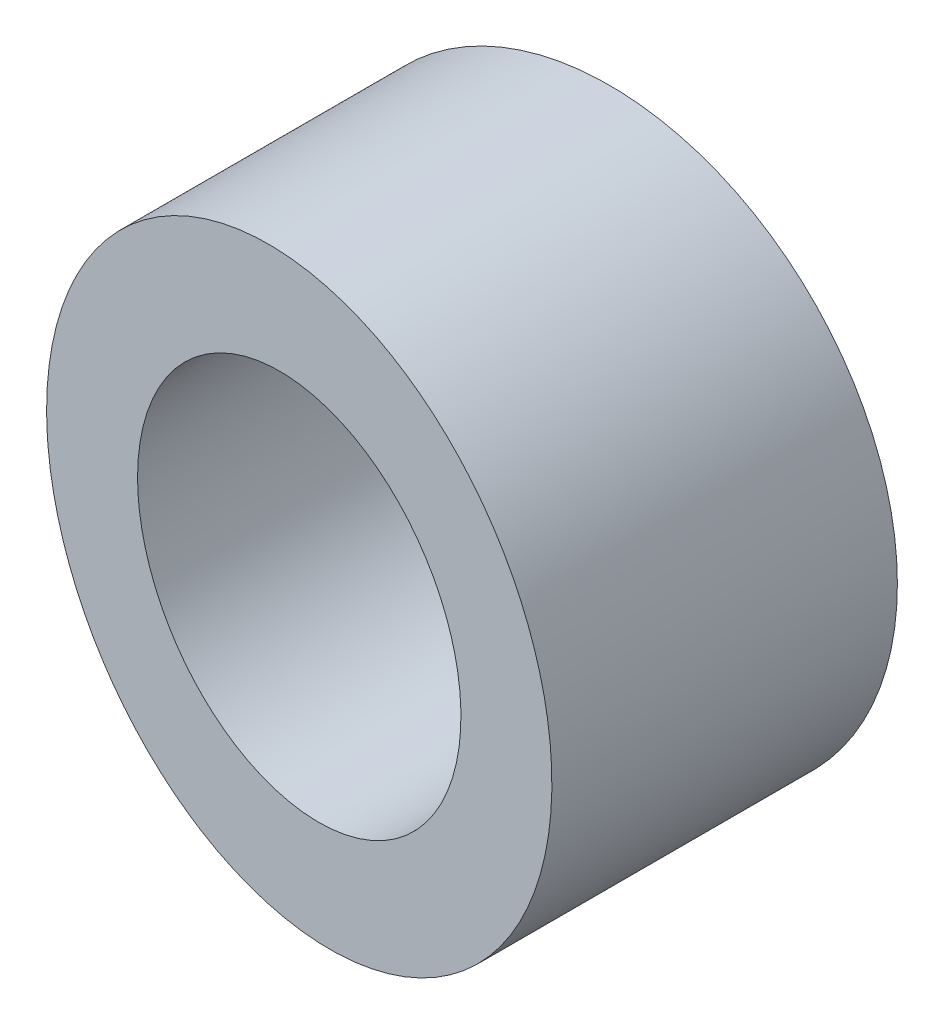
SolidWorks part; units mm, degrees
ref_plane "Front Plane" through (0, 0, 0) normal (0, 0, 1) x (1, 0, 0)
ref_plane "Top Plane" through (0, 0, 0) normal (0, 1, 0) x (1, 0, 0)
ref_plane "Right Plane" through (0, 0, 0) normal (1, 0, 0) x (0, 0, -1)
sketch "Sketch1" plane through (0, 0, 0) normal (0, 0, 1) x (1, 0, 0)
  circle A0 centre (0, 0) radius 12.5
  circle A1 centre (0, 0) radius 8
  dimension "D1" = 25
  dimension "D2" = 16
extrude "Boss-Extrude1" add sketch "Sketch1" along normal blind 15
sketch "Sketch2" plane through (0, 0, 0) normal (0, 1, 0) x (1, 0, 0)
  line L0 (-135.4872, 3.1284) -> (64.5128, -21.3716)
  line L1 (64.5128, -21.3716) -> (64.5128, -148.3716)
  line L2 (64.5128, -148.3716) -> (-135.4872, -172.8716)
  line L3 (-135.4872, -172.8716) -> (-135.4872, 3.1284)
  line L4 (-135.4872, -84.8716) -> (64.5128, -84.8716) construction
  line L5 (0, 0) -> (0, -13.4688) construction
  dimension "D1" = 127
  dimension "D2" = 176
  dimension "D3" = 200
  dimension "D4" = 136.5
extrude "Cut-Extrude1" cut sketch "Sketch2" against normal mid plane 206
